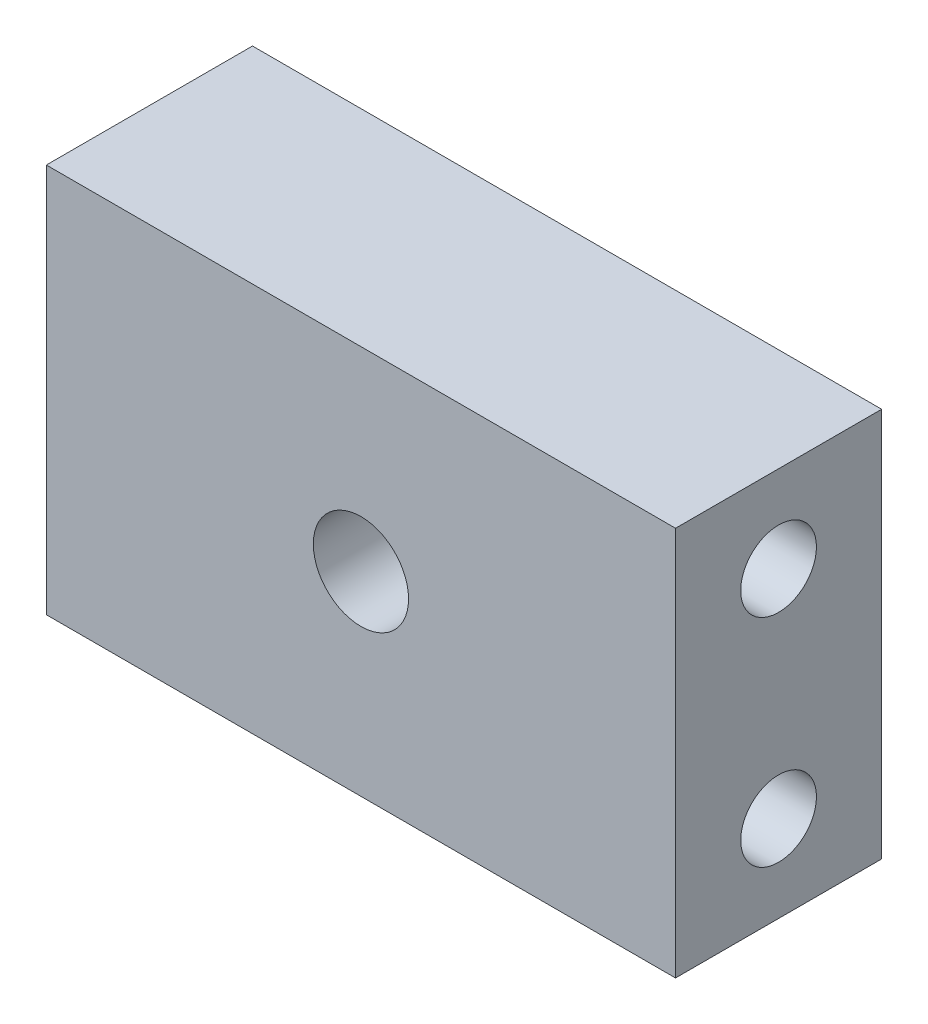
SolidWorks part; units mm, degrees
material "6061 Alloy"
ref_plane "Front Plane" through (0, 0, 0) normal (0, 0, 1) x (1, 0, 0)
ref_plane "Top Plane" through (0, 0, 0) normal (0, 1, 0) x (1, 0, 0)
ref_plane "Right Plane" through (0, 0, 0) normal (1, 0, 0) x (0, 0, -1)
sketch "Sketch1" plane through (0, 0, 0) normal (0, 0, 1) x (1, 0, 0)
  line L1 (-14.5375, 9) -> (14.5375, 9)
  line L2 (-14.5375, 9) -> (-14.5375, -9)
  line L3 (-14.5375, -9) -> (14.5375, -9)
  line L4 (14.5375, 9) -> (14.5375, -9)
  line L5 (0, -9) -> (0, 9) construction
  line L6 (-14.5375, 0) -> (14.5375, 0) construction
  point P0 (0, 0)
  dimension "D1" = 29.075
  dimension "D2" = 18
extrude "3/8" add sketch "Sketch1" along normal blind 9.525
sketch "Sketch2" plane through (-14.5375, 0, 0) normal (-1, 0, 0) x (0, 0, 1)
  line L0 (4.7625, 9) -> (4.7625, -9) construction
  line L1 (9.525, 9) -> (0, 9) construction
  line L2 (9.525, -9) -> (0, -9) construction
  line L3 (0, 0) -> (9.525, 0) construction
  line L4 (9.525, 9) -> (9.525, -9) construction
  circle A0 centre (4.7625, 5) radius 1.75
  circle A1 centre (4.7625, -5) radius 1.75
  dimension "D2" = 3.5
  dimension "D1" = 5
extrude "M4_DRILL" cut sketch "Sketch2" against normal blind 8
sketch "Sketch3" plane through (14.5375, 0, 0) normal (1, 0, 0) x (0, 0, -1)
  circle A0 centre (-4.7625, -5) radius 1.75 construction
  circle A1 centre (-4.7625, 5) radius 1.75 construction
  circle A2 centre (-4.7625, -5) radius 1.75
  circle A3 centre (-4.7625, 5) radius 1.75
extrude "M4_DRILL2" cut sketch "Sketch3" against normal blind 8
sketch "Sketch5" plane through (0, 0, 0) normal (0, 0, -1) x (-1, 0, 0)
  circle A0 centre (0, 0) radius 2.2
  dimension "D1" = 4.4
extrude "M5_DRILL" cut sketch "Sketch5" against normal up to surface (9.525 mm away) up to face at (0, 0, 9.525)
